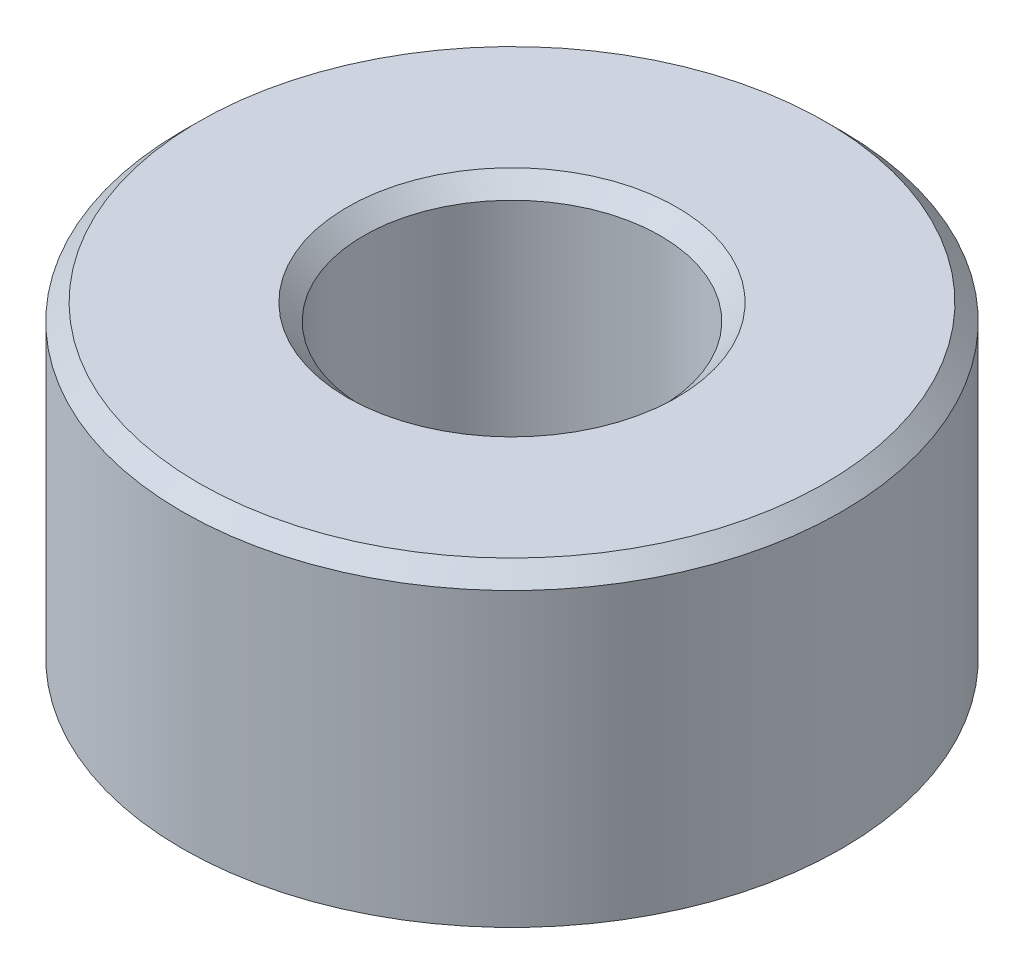
SolidWorks part; units mm, degrees
material "PET-G"
ref_plane "Front Plane" through (0, 0, 0) normal (0, 0, 1) x (1, 0, 0)
ref_plane "Top Plane" through (0, 0, 0) normal (0, 1, 0) x (1, 0, 0)
ref_plane "Right Plane" through (0, 0, 0) normal (1, 0, 0) x (0, 0, -1)
sketch "Sketch1" plane through (0, 0, 0) normal (0, 1, 0) x (1, 0, 0)
  circle A0 centre (0, 0) radius 4.5
  circle A1 centre (0, 0) radius 10
  dimension "D1" = 9
  dimension "D2" = 20
extrude "Body" add sketch "Sketch1" along normal blind 9.35
chamfer "Chamfer1" distance 0.5 angle 45 2 edges at (0, 9.35, 10) (0, 9.35, 4.5)
